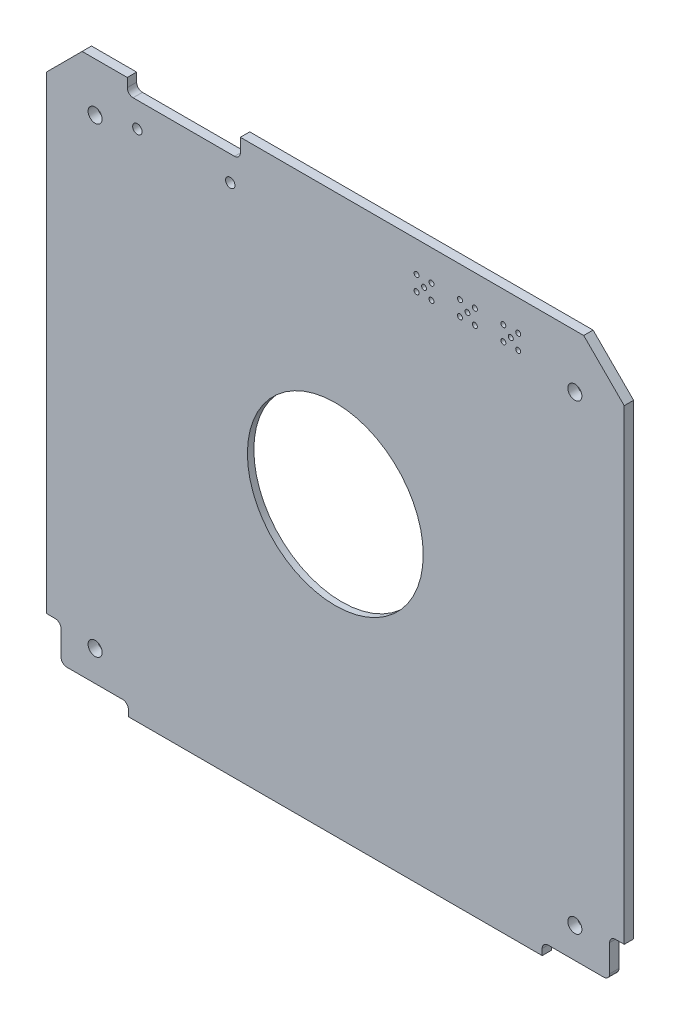
SolidWorks part; units mm, degrees
ref_plane "Front Plane" through (0, 0, 0) normal (0, 0, 1) x (1, 0, 0)
ref_plane "Top Plane" through (0, 0, 0) normal (0, 1, 0) x (1, 0, 0)
ref_plane "Right Plane" through (0, 0, 0) normal (1, 0, 0) x (0, 0, -1)
ref_plane "Plane1" through (0, 0, -0.0125) normal (0, 0, -1) x (-1, 0, 0)
sketch "Sketch1" plane through (0, 0, -0.0125) normal (0, 0, -1) x (-1, 0, 0)
  line L0 (-49.3, 46.115) -> (-49.3, -49.065)
  line L1 (-49.3, -49.065) -> (49.3, -49.065)
  line L2 (49.3, -49.065) -> (49.3, 46.115)
  line L3 (49.3, 46.115) -> (-49.3, 46.115)
extrude "Boss-Extrude1" add sketch "Sketch1" against normal blind 1.6
hole_wizard "Hole1" positions "Sketch3" profile "Sketch2" legacy
sketch "Sketch3" plane through (0, 0, -0.0125) normal (0, 0, -1) x (-1, 0, 0)
  point P0 (-31.21, 40.87)
sketch "Sketch2" plane through (31.21, 40.87, -0.0125) normal (1, 0, 0) x (0, 1, 0)
  line L0 (0, 0) -> (0, 1.6)
  line L1 (0, 1.6) -> (0.425, 1.6)
  line L2 (0.425, 1.6) -> (0.425, 0)
  line L3 (0.425, 0) -> (0, 0)
  line L4 (0, 110) -> (0, -10) construction
  dimension "Diameter" = 0.85
  dimension "Depth" = 1.6
hole_wizard "Hole2" positions "Sketch5" profile "Sketch4" legacy
sketch "Sketch5" plane through (0, 0, -0.0125) normal (0, 0, -1) x (-1, 0, 0)
  point P0 (-28.67, 40.87)
sketch "Sketch4" plane through (28.67, 40.87, -0.0125) normal (1, 0, 0) x (0, 1, 0)
  line L0 (0, 0) -> (0, 1.6)
  line L1 (0, 1.6) -> (0.425, 1.6)
  line L2 (0.425, 1.6) -> (0.425, 0)
  line L3 (0.425, 0) -> (0, 0)
  line L4 (0, 110) -> (0, -10) construction
  dimension "Diameter" = 0.85
  dimension "Depth" = 1.6
hole_wizard "Hole3" positions "Sketch7" profile "Sketch6" legacy
sketch "Sketch7" plane through (0, 0, -0.0125) normal (0, 0, -1) x (-1, 0, 0)
  point P0 (-29.94, 39.6)
sketch "Sketch6" plane through (29.94, 39.6, -0.0125) normal (1, 0, 0) x (0, 1, 0)
  line L0 (0, 0) -> (0, 1.6)
  line L1 (0, 1.6) -> (0.425, 1.6)
  line L2 (0.425, 1.6) -> (0.425, 0)
  line L3 (0.425, 0) -> (0, 0)
  line L4 (0, 110) -> (0, -10) construction
  dimension "Diameter" = 0.85
  dimension "Depth" = 1.6
hole_wizard "Hole4" positions "Sketch9" profile "Sketch8" legacy
sketch "Sketch9" plane through (0, 0, -0.0125) normal (0, 0, -1) x (-1, 0, 0)
  point P0 (-31.21, 38.33)
sketch "Sketch8" plane through (31.21, 38.33, -0.0125) normal (1, 0, 0) x (0, 1, 0)
  line L0 (0, 0) -> (0, 1.6)
  line L1 (0, 1.6) -> (0.425, 1.6)
  line L2 (0.425, 1.6) -> (0.425, 0)
  line L3 (0.425, 0) -> (0, 0)
  line L4 (0, 110) -> (0, -10) construction
  dimension "Diameter" = 0.85
  dimension "Depth" = 1.6
hole_wizard "Hole5" positions "Sketch11" profile "Sketch10" legacy
sketch "Sketch11" plane through (0, 0, -0.0125) normal (0, 0, -1) x (-1, 0, 0)
  point P0 (-28.67, 38.33)
sketch "Sketch10" plane through (28.67, 38.33, -0.0125) normal (1, 0, 0) x (0, 1, 0)
  line L0 (0, 0) -> (0, 1.6)
  line L1 (0, 1.6) -> (0.425, 1.6)
  line L2 (0.425, 1.6) -> (0.425, 0)
  line L3 (0.425, 0) -> (0, 0)
  line L4 (0, 110) -> (0, -10) construction
  dimension "Diameter" = 0.85
  dimension "Depth" = 1.6
hole_wizard "Hole6" positions "Sketch13" profile "Sketch12" legacy
sketch "Sketch13" plane through (0, 0, -0.0125) normal (0, 0, -1) x (-1, 0, 0)
  point P0 (-23.81, 40.87)
sketch "Sketch12" plane through (23.81, 40.87, -0.0125) normal (1, 0, 0) x (0, 1, 0)
  line L0 (0, 0) -> (0, 1.6)
  line L1 (0, 1.6) -> (0.425, 1.6)
  line L2 (0.425, 1.6) -> (0.425, 0)
  line L3 (0.425, 0) -> (0, 0)
  line L4 (0, 110) -> (0, -10) construction
  dimension "Diameter" = 0.85
  dimension "Depth" = 1.6
hole_wizard "Hole7" positions "Sketch15" profile "Sketch14" legacy
sketch "Sketch15" plane through (0, 0, -0.0125) normal (0, 0, -1) x (-1, 0, 0)
  point P0 (-21.27, 40.87)
sketch "Sketch14" plane through (21.27, 40.87, -0.0125) normal (1, 0, 0) x (0, 1, 0)
  line L0 (0, 0) -> (0, 1.6)
  line L1 (0, 1.6) -> (0.425, 1.6)
  line L2 (0.425, 1.6) -> (0.425, 0)
  line L3 (0.425, 0) -> (0, 0)
  line L4 (0, 110) -> (0, -10) construction
  dimension "Diameter" = 0.85
  dimension "Depth" = 1.6
hole_wizard "Hole8" positions "Sketch17" profile "Sketch16" legacy
sketch "Sketch17" plane through (0, 0, -0.0125) normal (0, 0, -1) x (-1, 0, 0)
  point P0 (-22.54, 39.6)
sketch "Sketch16" plane through (22.54, 39.6, -0.0125) normal (1, 0, 0) x (0, 1, 0)
  line L0 (0, 0) -> (0, 1.6)
  line L1 (0, 1.6) -> (0.425, 1.6)
  line L2 (0.425, 1.6) -> (0.425, 0)
  line L3 (0.425, 0) -> (0, 0)
  line L4 (0, 110) -> (0, -10) construction
  dimension "Diameter" = 0.85
  dimension "Depth" = 1.6
hole_wizard "Hole9" positions "Sketch19" profile "Sketch18" legacy
sketch "Sketch19" plane through (0, 0, -0.0125) normal (0, 0, -1) x (-1, 0, 0)
  point P0 (-23.81, 38.33)
sketch "Sketch18" plane through (23.81, 38.33, -0.0125) normal (1, 0, 0) x (0, 1, 0)
  line L0 (0, 0) -> (0, 1.6)
  line L1 (0, 1.6) -> (0.425, 1.6)
  line L2 (0.425, 1.6) -> (0.425, 0)
  line L3 (0.425, 0) -> (0, 0)
  line L4 (0, 110) -> (0, -10) construction
  dimension "Diameter" = 0.85
  dimension "Depth" = 1.6
hole_wizard "Hole10" positions "Sketch21" profile "Sketch20" legacy
sketch "Sketch21" plane through (0, 0, -0.0125) normal (0, 0, -1) x (-1, 0, 0)
  point P0 (-21.27, 38.33)
sketch "Sketch20" plane through (21.27, 38.33, -0.0125) normal (1, 0, 0) x (0, 1, 0)
  line L0 (0, 0) -> (0, 1.6)
  line L1 (0, 1.6) -> (0.425, 1.6)
  line L2 (0.425, 1.6) -> (0.425, 0)
  line L3 (0.425, 0) -> (0, 0)
  line L4 (0, 110) -> (0, -10) construction
  dimension "Diameter" = 0.85
  dimension "Depth" = 1.6
hole_wizard "Hole11" positions "Sketch23" profile "Sketch22" legacy
sketch "Sketch23" plane through (0, 0, -0.0125) normal (0, 0, -1) x (-1, 0, 0)
  point P0 (-16.41, 40.87)
sketch "Sketch22" plane through (16.41, 40.87, -0.0125) normal (1, 0, 0) x (0, 1, 0)
  line L0 (0, 0) -> (0, 1.6)
  line L1 (0, 1.6) -> (0.425, 1.6)
  line L2 (0.425, 1.6) -> (0.425, 0)
  line L3 (0.425, 0) -> (0, 0)
  line L4 (0, 110) -> (0, -10) construction
  dimension "Diameter" = 0.85
  dimension "Depth" = 1.6
hole_wizard "Hole12" positions "Sketch25" profile "Sketch24" legacy
sketch "Sketch25" plane through (0, 0, -0.0125) normal (0, 0, -1) x (-1, 0, 0)
  point P0 (-13.87, 40.87)
sketch "Sketch24" plane through (13.87, 40.87, -0.0125) normal (1, 0, 0) x (0, 1, 0)
  line L0 (0, 0) -> (0, 1.6)
  line L1 (0, 1.6) -> (0.425, 1.6)
  line L2 (0.425, 1.6) -> (0.425, 0)
  line L3 (0.425, 0) -> (0, 0)
  line L4 (0, 110) -> (0, -10) construction
  dimension "Diameter" = 0.85
  dimension "Depth" = 1.6
hole_wizard "Hole13" positions "Sketch27" profile "Sketch26" legacy
sketch "Sketch27" plane through (0, 0, -0.0125) normal (0, 0, -1) x (-1, 0, 0)
  point P0 (-15.14, 39.6)
sketch "Sketch26" plane through (15.14, 39.6, -0.0125) normal (1, 0, 0) x (0, 1, 0)
  line L0 (0, 0) -> (0, 1.6)
  line L1 (0, 1.6) -> (0.425, 1.6)
  line L2 (0.425, 1.6) -> (0.425, 0)
  line L3 (0.425, 0) -> (0, 0)
  line L4 (0, 110) -> (0, -10) construction
  dimension "Diameter" = 0.85
  dimension "Depth" = 1.6
hole_wizard "Hole14" positions "Sketch29" profile "Sketch28" legacy
sketch "Sketch29" plane through (0, 0, -0.0125) normal (0, 0, -1) x (-1, 0, 0)
  point P0 (-16.41, 38.33)
sketch "Sketch28" plane through (16.41, 38.33, -0.0125) normal (1, 0, 0) x (0, 1, 0)
  line L0 (0, 0) -> (0, 1.6)
  line L1 (0, 1.6) -> (0.425, 1.6)
  line L2 (0.425, 1.6) -> (0.425, 0)
  line L3 (0.425, 0) -> (0, 0)
  line L4 (0, 110) -> (0, -10) construction
  dimension "Diameter" = 0.85
  dimension "Depth" = 1.6
hole_wizard "Hole15" positions "Sketch31" profile "Sketch30" legacy
sketch "Sketch31" plane through (0, 0, -0.0125) normal (0, 0, -1) x (-1, 0, 0)
  point P0 (-13.87, 38.33)
sketch "Sketch30" plane through (13.87, 38.33, -0.0125) normal (1, 0, 0) x (0, 1, 0)
  line L0 (0, 0) -> (0, 1.6)
  line L1 (0, 1.6) -> (0.425, 1.6)
  line L2 (0.425, 1.6) -> (0.425, 0)
  line L3 (0.425, 0) -> (0, 0)
  line L4 (0, 110) -> (0, -10) construction
  dimension "Diameter" = 0.85
  dimension "Depth" = 1.6
hole_wizard "Hole16" positions "Sketch33" profile "Sketch32" legacy
sketch "Sketch33" plane through (0, 0, -0.0125) normal (0, 0, -1) x (-1, 0, 0)
  point P0 (17.925, 38.54)
sketch "Sketch32" plane through (-17.925, 38.54, -0.0125) normal (1, 0, 0) x (0, 1, 0)
  line L0 (0, 0) -> (0, 1.6)
  line L1 (0, 1.6) -> (0.8, 1.6)
  line L2 (0.8, 1.6) -> (0.8, 0)
  line L3 (0.8, 0) -> (0, 0)
  line L4 (0, 110) -> (0, -10) construction
  dimension "Diameter" = 1.6
  dimension "Depth" = 1.6
hole_wizard "Hole17" positions "Sketch35" profile "Sketch34" legacy
sketch "Sketch35" plane through (0, 0, -0.0125) normal (0, 0, -1) x (-1, 0, 0)
  point P0 (33.775, 38.54)
sketch "Sketch34" plane through (-33.775, 38.54, -0.0125) normal (1, 0, 0) x (0, 1, 0)
  line L0 (0, 0) -> (0, 1.6)
  line L1 (0, 1.6) -> (0.8, 1.6)
  line L2 (0.8, 1.6) -> (0.8, 0)
  line L3 (0.8, 0) -> (0, 0)
  line L4 (0, 110) -> (0, -10) construction
  dimension "Diameter" = 1.6
  dimension "Depth" = 1.6
hole_wizard "#2 Clearance Hole1" positions "Sketch37" profile "Sketch36" hole size "#2" standard "ANSI Inch"
sketch "Sketch37" plane through (0, 0, -0.0125) normal (0, 0, -1) x (-1, 0, 0)
  point P0 (40.9862, 36.9926)
sketch "Sketch36" plane through (-40.9862, 36.9926, -0.0125) normal (1, 0, 0) x (0, 1, 0)
  line L0 (0, 0) -> (0, 1.6)
  line L1 (0, 1.6) -> (1.2, 1.6)
  line L2 (1.2, 1.6) -> (1.2, 0)
  line L5 (1.2, 0) -> (0, 0)
  line L11 (0, -6.35) -> (0, 107.95) construction
  dimension "Thru Hole Dia." = 2.4
  dimension "Thru Hole Depth" = 1.6
hole_wizard "#2 Clearance Hole2" positions "Sketch39" profile "Sketch38" hole size "#2" standard "ANSI Inch"
sketch "Sketch39" plane through (0, 0, -0.0125) normal (0, 0, -1) x (-1, 0, 0)
  point P0 (-40.8728, 36.9926)
sketch "Sketch38" plane through (40.8728, 36.9926, -0.0125) normal (1, 0, 0) x (0, 1, 0)
  line L0 (0, 0) -> (0, 1.6)
  line L1 (0, 1.6) -> (1.2, 1.6)
  line L2 (1.2, 1.6) -> (1.2, 0)
  line L5 (1.2, 0) -> (0, 0)
  line L11 (0, -6.35) -> (0, 107.95) construction
  dimension "Thru Hole Dia." = 2.4
  dimension "Thru Hole Depth" = 1.6
hole_wizard "#2 Clearance Hole3" positions "Sketch41" profile "Sketch40" hole size "#2" standard "ANSI Inch"
sketch "Sketch41" plane through (0, 0, -0.0125) normal (0, 0, -1) x (-1, 0, 0)
  point P0 (-40.8728, -41.8022)
sketch "Sketch40" plane through (40.8728, -41.8022, -0.0125) normal (1, 0, 0) x (0, 1, 0)
  line L0 (0, 0) -> (0, 1.6)
  line L1 (0, 1.6) -> (1.2, 1.6)
  line L2 (1.2, 1.6) -> (1.2, 0)
  line L5 (1.2, 0) -> (0, 0)
  line L11 (0, -6.35) -> (0, 107.95) construction
  dimension "Thru Hole Dia." = 2.4
  dimension "Thru Hole Depth" = 1.6
hole_wizard "#2 Clearance Hole4" positions "Sketch43" profile "Sketch42" hole size "#2" standard "ANSI Inch"
sketch "Sketch43" plane through (0, 0, -0.0125) normal (0, 0, -1) x (-1, 0, 0)
  point P0 (40.9862, -41.8022)
sketch "Sketch42" plane through (-40.9862, -41.8022, -0.0125) normal (1, 0, 0) x (0, 1, 0)
  line L0 (0, 0) -> (0, 1.6)
  line L1 (0, 1.6) -> (1.2, 1.6)
  line L2 (1.2, 1.6) -> (1.2, 0)
  line L5 (1.2, 0) -> (0, 0)
  line L11 (0, -6.35) -> (0, 107.95) construction
  dimension "Thru Hole Dia." = 2.4
  dimension "Thru Hole Depth" = 1.6
ref_plane "Plane2" through (0, 0, 0.4875) normal (0, 0, 1) x (1, 0, 0)
sketch "Sketch44" plane through (0, 0, 0.4875) normal (0, 0, 1) x (1, 0, 0)
  circle A0 centre (0, 0) radius 38.5
extrude "Cut-Extrude1" cut sketch "Sketch44" against normal up to next
hole_wizard "Hole18" positions "Sketch46" profile "Sketch45" legacy
sketch "Sketch46" plane through (0, 0, 1.5875) normal (0, 0, 1) x (1, 0, 0)
  point P0 (0, 0)
sketch "Sketch45" plane through (0, 0, 1.5875) normal (1, 0, 0) x (0, -1, 0)
  line L0 (0, 0) -> (0, 1.6)
  line L1 (0, 1.6) -> (15, 1.6)
  line L2 (15, 1.6) -> (15, 0)
  line L3 (15, 0) -> (0, 0)
  line L4 (0, 110) -> (0, -10) construction
  dimension "Diameter" = 30
  dimension "Depth" = 1.6
ref_plane "Plane3" through (0, -47, 0) normal (0, 1, 0) x (1, 0, 0)
sketch "Sketch47" plane through (0, -47, 0) normal (0, 1, 0) x (1, 0, 0)
  line L0 (49.3, 0.0125) -> (35.3, 0.0125)
  line L1 (35.3, 0.0125) -> (35.3, -1.5875)
  line L2 (35.3, -1.5875) -> (49.3, -1.5875)
  line L3 (49.3, -1.5875) -> (49.3, 0.0125)
extrude "Cut-Extrude2" cut sketch "Sketch47" against normal up to next
ref_plane "Plane4" through (46.8, 0, 0) normal (-1, 0, 0) x (0, -1, 0)
sketch "Sketch48" plane through (46.8, 0, 0) normal (-1, 0, 0) x (0, -1, 0)
  line L0 (47, 1.5875) -> (40.4, 1.5875)
  line L1 (40.4, 1.5875) -> (40.4, -0.0125)
  line L2 (40.4, -0.0125) -> (47, -0.0125)
  line L3 (47, -0.0125) -> (47, 1.5875)
extrude "Cut-Extrude3" cut sketch "Sketch48" against normal up to next
ref_plane "Plane5" through (-46.8, 0, 0) normal (1, 0, 0) x (0, 0, -1)
sketch "Sketch49" plane through (-46.8, 0, 0) normal (1, 0, 0) x (0, 0, -1)
  line L0 (0.0125, -49.065) -> (0.0125, -40.8)
  line L1 (0.0125, -40.8) -> (-1.5875, -40.8)
  line L2 (-1.5875, -40.8) -> (-1.5875, -49.065)
  line L3 (-1.5875, -49.065) -> (0.0125, -49.065)
extrude "Cut-Extrude4" cut sketch "Sketch49" against normal up to next
sketch "Sketch50" plane through (0, -47, 0) normal (0, 1, 0) x (1, 0, 0)
  line L0 (-35.3, 0.0125) -> (-46.8, 0.0125)
  line L1 (-46.8, 0.0125) -> (-46.8, -1.5875)
  line L2 (-46.8, -1.5875) -> (-35.3, -1.5875)
  line L3 (-35.3, -1.5875) -> (-35.3, 0.0125)
extrude "Cut-Extrude5" cut sketch "Sketch50" against normal up to next
ref_plane "Plane6" through (0, 45.3, 0) normal (0, -1, 0) x (1, 0, 0)
sketch "Sketch51" plane through (0, 45.3, 0) normal (0, -1, 0) x (1, 0, 0)
  line L0 (-16.2, 1.5875) -> (-49.3, 1.5875)
  line L1 (-49.3, 1.5875) -> (-49.3, -0.0125)
  line L2 (-49.3, -0.0125) -> (-16.2, -0.0125)
  line L3 (-16.2, -0.0125) -> (-16.2, 1.5875)
extrude "Cut-Extrude6" cut sketch "Sketch51" against normal up to next
ref_plane "Plane7" through (0, 42.8, 0) normal (0, -1, 0) x (1, 0, 0)
sketch "Sketch52" plane through (0, 42.8, 0) normal (0, -1, 0) x (1, 0, 0)
  line L0 (-35.5, -0.0125) -> (-16.2, -0.0125)
  line L1 (-16.2, -0.0125) -> (-16.2, 1.5875)
  line L2 (-16.2, 1.5875) -> (-35.5, 1.5875)
  line L3 (-35.5, 1.5875) -> (-35.5, -0.0125)
extrude "Cut-Extrude7" cut sketch "Sketch52" against normal up to next
chamfer "Chamfer1" distance 6.915 angle 45 1 edges at (49.3, 46.115, 0.7875)
chamfer "Chamfer2" distance 6.1 angle 45 1 edges at (-49.3, 45.3, 0.7875)
fillet "Fillet1" radius 1 8 edges at (35.3, -47, 0.7875) (-46.8, -40.8, 0.7875) (-35.3, -47, 0.7875) (-16.2, 42.8, 0.7875) (-46.8, -47, 0.7875) (46.8, -47, 0.7875) (46.8, -40.4, 0.7875) (-35.5, 42.8, 0.7875)
